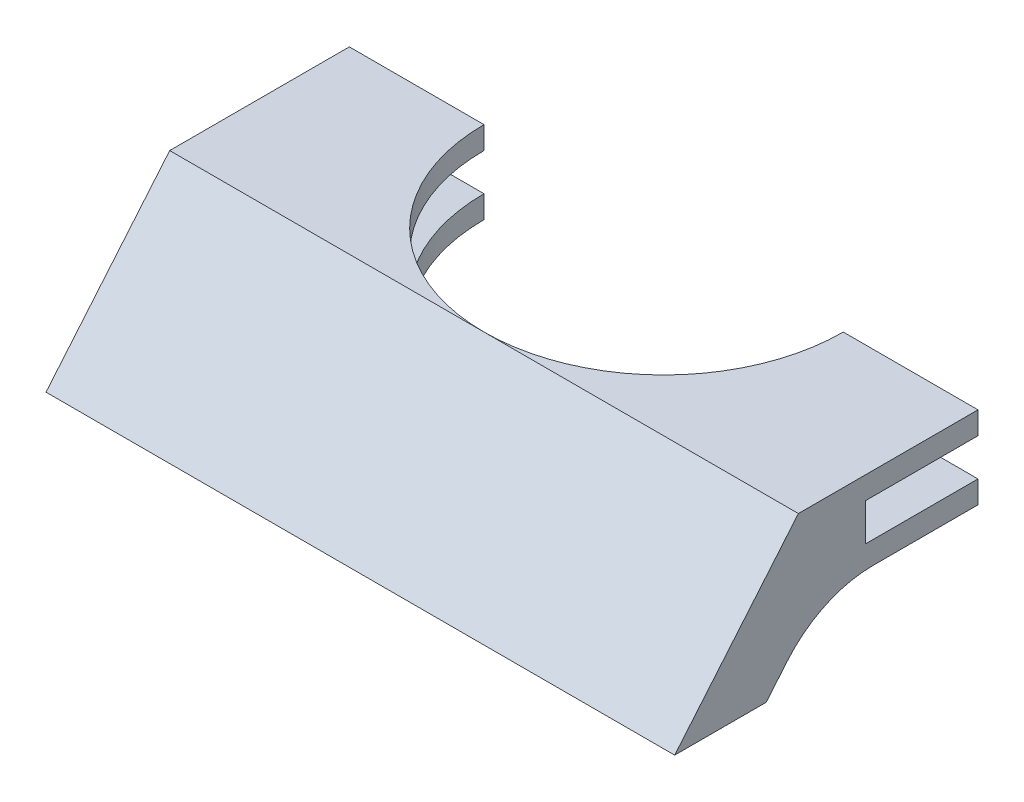
SolidWorks part; units mm, degrees
other "DetailItem1"
other "DetailItem2"
other "DetailItem3"
other "Markup1"
sketch "Sketch14" plane through (64.476, -2.1506, 13.6382) normal (1, 0, 0) x (0, 0, -1)
ref_plane "Front" through (0, 0, 0) normal (0, 0, 1) x (1, 0, 0)
ref_plane "Top" through (0, 0, 0) normal (0, 1, 0) x (1, 0, 0)
ref_plane "Right" through (0, 0, 0) normal (1, 0, 0) x (0, 0, -1)
sketch "Sketch1" plane through (0, 0, 0) normal (1, 0, 0) x (0, 0, -1)
  line L0 (-3.3196, 0) -> (19.4532, 0) construction
  line L5 (15.0959, 0) -> (15.0959, 52.657) construction
  line L8 (19.3959, 18.31) -> (22.0959, 18.31) construction
  line L9 (22.0959, 18.31) -> (22.0959, 38.31) construction
  line L11 (22.0959, 38.31) -> (24.0959, 38.31) construction
  line L12 (24.0959, 38.31) -> (24.0959, 54.81) construction
  line L36 (34.3959, 11.98) -> (71.8548, 11.98) construction
  line L37 (34.3959, 11.98) -> (34.3959, 8.8) construction
  line L38 (34.3959, 8.8) -> (71.8548, 8.8) construction
  line L41 (44.2459, 12.13) -> (34.2459, 12.13)
  line L45 (34.2459, 12.13) -> (34.2459, 8.8)
  line L46 (34.2459, 8.8) -> (44.2459, 8.8)
  line L47 (44.2459, 8.8) -> (44.2459, 6.8)
  line L48 (44.2459, 6.8) -> (30.2459, 6.8)
  line L49 (30.2459, 6.8) -> (25.3791, 1)
  line L50 (25.3791, 1) -> (17.2285, 1)
  line L51 (17.2285, 1) -> (28.2459, 14.13)
  line L52 (28.2459, 14.13) -> (44.2459, 14.13)
  line L53 (44.2459, 14.13) -> (44.2459, 12.13)
  circle A0 centre (0, 21.5) radius 21.5 construction
  circle A1 centre (22.0959, 38.31) radius 6.25 construction
  circle A5 centre (19.3959, 18.31) radius 2 construction
  circle A6 centre (24.0959, 54.81) radius 8 construction
  dimension "D2" = 12.5
  dimension "D4" = 26.33
  dimension "D7" = 3.18
  dimension "D8" = 2
  dimension "D10" = 20
  dimension "D12" = 43
  dimension "D17" = 2
  dimension "D19" = 16
  dimension "D20" = 4
  dimension "D22" = 4
  dimension "D15" = 16
  dimension "D3" = 38.31
  dimension "D5" = 7
  dimension "D6" = 12.3
  dimension "D9" = 0.15
  dimension "D11" = 2.7
  dimension "D13" = 0.15
  dimension "D14" = 3.33
  dimension "D16" = 10
  dimension "D18" = 16.5
  dimension "D21" = 1
  dimension "D23" = 50
extrude "Boss-Extrude1" add sketch "Sketch1" along normal blind 56
fillet "Fillet1" radius 10 1 edges at (28, 6.8, -30.2459)
sketch "Sketch15" plane through (0, 14.13, 0) normal (0, 1, 0) x (1, 0, 0)
  line L0 (56, 44.2459) -> (0, 44.2459) construction
  circle A0 centre (28, 44.2459) radius 16
extrude "Cut-Extrude1" cut sketch "Sketch15" against normal through all
move or copy body "Body-Move/Copy1" [suppressed] bodies to move or copy 107
sketch "Bend-Lines1" [suppressed] plane through (0, 0, 0) normal (0, 1, 0) x (1, 0, 0)
sketch "Bounding-Box1" [suppressed] plane through (0, 0, 0) normal (0, 1, 0) x (1, 0, 0)
sketch "Sketch9" [suppressed] plane through (0, 0, 0) normal (1, 0, 0) x (0, 0, -1)
  line L0 (30.8525, 47.8188) -> (32.8525, 47.8188) construction
  line L1 (36.0025, 47.8188) -> (27.7025, 47.8188) construction
  line L2 (30.8525, 48.3188) -> (32.8525, 48.3188)
  line L3 (30.8525, 47.3188) -> (32.8525, 47.3188)
  line L4 (30.8525, 34.8) -> (32.8525, 34.8) construction
  line L5 (36.0025, 34.8) -> (27.7025, 34.8) construction
  line L6 (30.8525, 35.3) -> (32.8525, 35.3)
  line L7 (30.8525, 34.3) -> (32.8525, 34.3)
  line L8 (16.0804, 3.8848) -> (20.4105, 6.3848) construction
  line L9 (11.7502, 1.3848) -> (24.7406, 8.8848) construction
  line L10 (15.8304, 4.3178) -> (20.1605, 6.8178)
  line L11 (16.3304, 3.4518) -> (20.6605, 5.9518)
  arc A0 (30.8525, 48.3188) -> (30.8525, 47.3188) centre (30.8525, 47.8188) ccw
  arc A1 (32.8525, 47.3188) -> (32.8525, 48.3188) centre (32.8525, 47.8188) ccw
  arc A2 (30.8525, 35.3) -> (30.8525, 34.3) centre (30.8525, 34.8) ccw
  arc A3 (32.8525, 34.3) -> (32.8525, 35.3) centre (32.8525, 34.8) ccw
  arc A4 (15.8304, 4.3178) -> (16.3304, 3.4518) centre (16.0804, 3.8848) ccw
  arc A5 (20.6605, 5.9518) -> (20.1605, 6.8178) centre (20.4105, 6.3848) ccw
  point P4 (31.8525, 47.8188)
  point P9 (31.8525, 34.8)
  point P22 (18.2454, 5.1348)
  dimension "D1" = 1
  dimension "D2" = 2
  dimension "D3" = 1
  dimension "D4" = 5
equation "\"d1\"= 21mm"
equation "\"H\"= 64.8mm + 5mm"
equation "\"D\"= 22mm"
equation "\"H1\"= 38mm"
equation "\"H2\"= \"H\" - \"H1\""
equation "\"weld diameter\"= 6.8mm"
equation "\"bend allowance\"= 3mm"
equation "\"chipper-width\"= 66mm"
equation "\"D7\" = \"chipper-width\" / 2"
